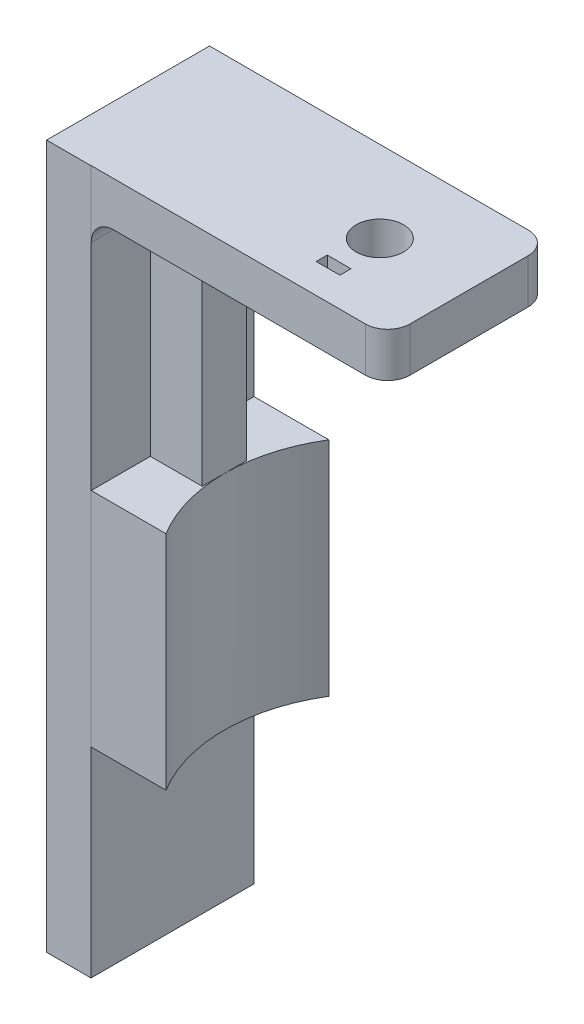
SolidWorks part; units mm, degrees
ref_plane "Front Plane" through (0, 0, 0) normal (0, 0, 1) x (1, 0, 0)
ref_plane "Top Plane" through (0, 0, 0) normal (0, 1, 0) x (1, 0, 0)
ref_plane "Right Plane" through (0, 0, 0) normal (1, 0, 0) x (0, 0, -1)
sketch "Sketch2" plane through (0, 0, 0) normal (0, 1, 0) x (1, 0, 0)
  line L0 (0, 0) -> (-28, 0)
  line L2 (-34, 11) -> (-28, 11)
  line L3 (-34, 11) -> (-34, -11)
  line L4 (-34, -11) -> (-28, -11)
  line L5 (-28, 11) -> (-28, -11)
extrude "Boss-Extrude2" add sketch "Sketch2" along normal blind 95 contours L5 L2 L3 L4
sketch "Sketch3" plane through (0, 95, 0) normal (0, 1, 0) x (1, 0, 0)
  line L1 (-28, 11) -> (9.0413, 11)
  line L2 (-28, 11) -> (-28, -10.9784)
  line L3 (-28, -10.9784) -> (9.0413, -10.9784)
  line L4 (12.0413, 8) -> (12.0413, -7.9784)
  line L6 (-1.6, -5.5) -> (1.6, -5.5)
  line L7 (-1.6, -5.5) -> (-1.6, -7)
  line L8 (-1.6, -7) -> (1.6, -7)
  line L9 (1.6, -5.5) -> (1.6, -7)
  arc A0 (12.0413, 8) -> (9.0413, 11) centre (9.0413, 8) ccw
  arc A1 (12.0413, -7.9784) -> (9.0413, -10.9784) centre (9.0413, -7.9784) cw
  circle A2 centre (0, 0) radius 3.2
  dimension "D1" = 3
  dimension "D2" = 3
extrude "Boss-Extrude3" add sketch "Sketch3" against normal blind 6
sketch "Sketch4" plane through (-28, 0, 0) normal (1, 0, 0) x (0, 0, -1)
  line L1 (-2.9892, 89) -> (3.0108, 89)
  line L2 (-2.9892, 89) -> (-2.9892, 27)
  line L3 (-2.9892, 27) -> (3.0108, 27)
  line L4 (3.0108, 89) -> (3.0108, 27)
extrude "Boss-Extrude4" add sketch "Sketch4" along normal blind 7
sketch "Sketch5" plane through (0, 27, 0) normal (0, -1, 0) x (1, 0, 0)
  line L1 (-28, 10.9784) -> (-17.9018, 10.9784)
  line L2 (-28, 10.9784) -> (-28, -11)
  line L3 (-28, -11) -> (-17.8885, -11)
  arc A1 (-17.9018, 10.9784) -> (-17.8885, -11) centre (0, 0) ccw
extrude "Boss-Extrude5" add sketch "Sketch5" against normal blind 30
fillet "Fillet4" radius 3 3 edges at (-28, 89, 6.9838) (-28, 89, -7.0054) (-21, 89, -0.0108)
